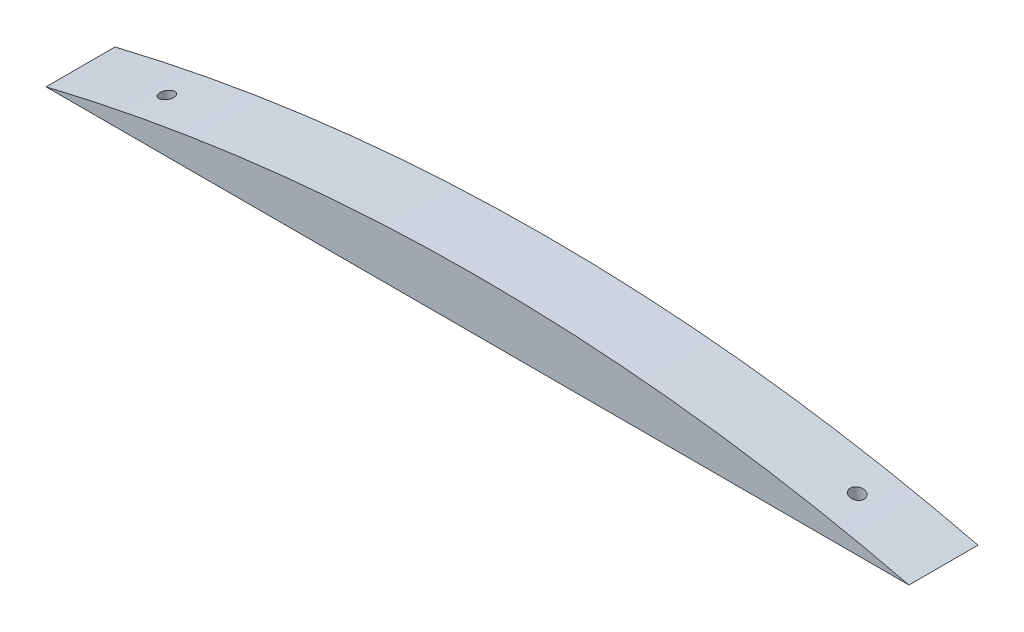
SolidWorks part; units mm, degrees
ref_plane "Front Plane" through (0, 0, 0) normal (0, 0, 1) x (1, 0, 0)
ref_plane "Top Plane" through (0, 0, 0) normal (0, 1, 0) x (1, 0, 0)
ref_plane "Right Plane" through (0, 0, 0) normal (1, 0, 0) x (0, 0, -1)
sketch "Sketch1" plane through (0, 0, 0) normal (0, 0, 1) x (1, 0, 0)
  line L0 (-158.75, 0) -> (158.75, 0)
  line L1 (-150.8125, 0) -> (150.8125, 0)
  arc A0 (-158.75, 0) -> (158.75, 0) centre (0, -653.1377) cw
  point P4 (0, 0)
  point P8 (0, 0)
  dimension "D1" = 317.5
extrude "Boss-Extrude3" add sketch "Sketch1" along normal blind 25.4 contours A0 L0
sketch "Sketch2" plane through (0, 0, 0) normal (0, -1, 0) x (1, 0, 0)
  line L0 (0, 25.4) -> (0, 0) construction
  line L1 (-158.75, 25.4) -> (158.75, 25.4) construction
  line L2 (-180.975, 12.7) -> (180.975, 12.7)
  circle A0 centre (-180.975, 12.7) radius 4.7625
  circle A1 centre (180.975, 12.7) radius 4.7625
  point P8 (0, 12.7)
  dimension "D1" = 9.525
  dimension "D2" = 9.525
extrude "Cut-Extrude1" cut sketch "Sketch2" against normal blind 25.4
sketch "Sketch3" plane through (0, 0, 0) normal (0, -1, 0) x (1, 0, 0)
  line L0 (-158.75, 12.7) -> (158.75, 12.7) construction
  line L1 (-158.75, 25.4) -> (-158.75, 0) construction
  line L2 (158.75, 25.4) -> (158.75, 0) construction
  line L3 (-127, 12.7) -> (127, 12.7)
  circle A0 centre (-127, 12.7) radius 2.5527
  circle A1 centre (127, 12.7) radius 2.5527
  point P9 (0, 12.7)
  dimension "D1" = 5.1054
  dimension "D2" = 5.1054
extrude "Cut-Extrude2" cut sketch "Sketch3" against normal blind 12.7 contours A1 | A0
